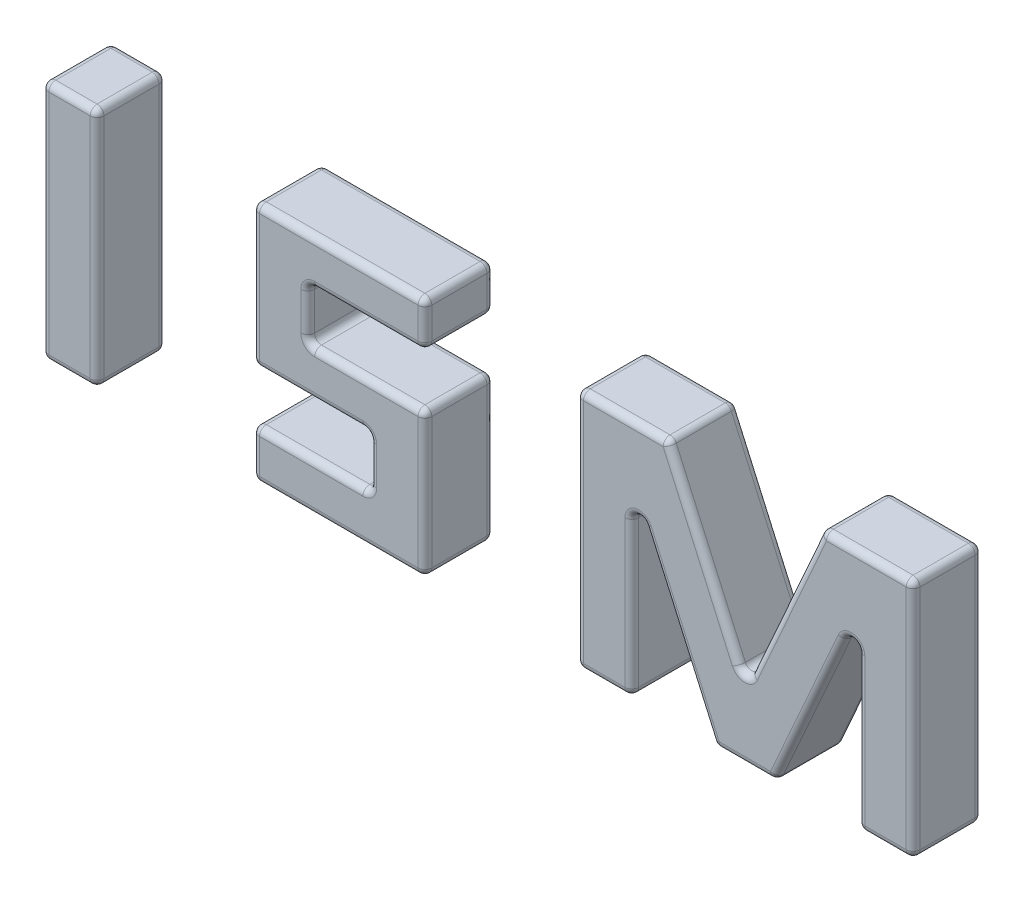
SolidWorks part; units mm, degrees
ref_plane "Front Plane" through (0, 0, 0) normal (0, 0, 1) x (1, 0, 0)
ref_plane "Top Plane" through (0, 0, 0) normal (0, 1, 0) x (1, 0, 0)
ref_plane "Right Plane" through (0, 0, 0) normal (1, 0, 0) x (0, 0, -1)
sketch "Sketch1" plane through (0, 0, 0) normal (0, 0, 1) x (1, 0, 0)
  line L0 (0, 0) -> (97.6044, 0) construction
  line L1 (0, 0) -> (0, 35) construction
  line L2 (0, 0) -> (0, 35)
  line L3 (0, 35) -> (8, 35)
  line L4 (8, 35) -> (8, 0)
  line L5 (8, 0) -> (0, 0)
  line L6 (55.565, 35) -> (30.565, 35)
  line L7 (0, 35) -> (130, 35) construction
  line L8 (130, 35) -> (130, 0) construction
  line L9 (30.565, 0) -> (55.565, 0)
  line L10 (55.565, 0) -> (55.565, 21)
  line L11 (30.565, 35) -> (30.565, 14.5)
  line L12 (55.565, 35) -> (55.565, 28.5)
  line L13 (55.565, 28.5) -> (38.565, 28.5)
  line L14 (38.565, 28.5) -> (38.565, 21)
  line L15 (38.565, 21) -> (55.565, 21)
  line L16 (30.565, 14.5) -> (47.565, 14.5)
  line L17 (47.565, 14.5) -> (47.565, 7)
  line L18 (47.565, 7) -> (30.565, 7)
  line L19 (30.565, 7) -> (30.565, 0)
  line L20 (85.5802, 27.0067) -> (97.6044, 0)
  line L21 (55.565, 35) -> (77.565, 35)
  line L22 (77.565, 35) -> (77.565, 0)
  line L23 (77.565, 0) -> (85.5802, 0)
  line L24 (85.5802, 0) -> (85.5802, 27.0067)
  line L25 (106.3615, 0) -> (130, 0) construction
  line L28 (90.7785, 35) -> (77.565, 35)
  line L29 (97.6044, 0) -> (106.3615, 0)
  line L30 (113.1874, 35) -> (126.4008, 35)
  line L32 (90.7785, 35) -> (101.9829, 9.8344)
  line L33 (113.1874, 35) -> (101.9829, 9.8344)
  line L34 (118.3856, 27.0067) -> (106.3615, 0)
  line L35 (118.3856, 0) -> (118.3856, 27.0067)
  line L36 (126.4008, 0) -> (118.3856, 0)
  line L37 (126.4008, 35) -> (126.4008, 0)
extrude "Boss-Extrude1" add sketch "Sketch1" along normal blind 10 contours L5 L4 L3 L2 | L18 L19 L9 L10 L15 L14 L13 L12 L6 L11 L16 L17 | L37 L30 L33 L32 L28 L22 L23 L24 L20 L29 L34 L35 L36
fillet "Fillet1" radius 1 12 edges at (8, 0, 5) (8, 35, 5) (0, 35, 5) (0, 0, 5) (0, 17.5, 10) (4, 35, 10) (8, 17.5, 10) (4, 0, 10) (0, 17.5, 0) (4, 35, 0) (8, 17.5, 0) (4, 0, 0)
fillet "Fillet2" radius 1 36 edges at (30.565, 7, 5) (30.565, 0, 5) (55.565, 0, 5) (55.565, 21, 5) (38.565, 21, 5) (38.565, 28.5, 5) (55.565, 28.5, 5) (55.565, 35, 5) (30.565, 35, 5) (30.565, 14.5, 5) (47.565, 14.5, 5) (47.565, 7, 5) (47.565, 10.75, 10) (39.065, 14.5, 10) (30.565, 24.75, 10) (43.065, 35, 10) (55.565, 31.75, 10) (47.065, 28.5, 10) (38.565, 24.75, 10) (47.065, 21, 10) (55.565, 10.5, 10) (43.065, 0, 10) (30.565, 3.5, 10) (39.065, 7, 10) (47.565, 10.75, 0) (39.065, 14.5, 0) (30.565, 24.75, 0) (43.065, 35, 0) (55.565, 31.75, 0) (47.065, 28.5, 0) (38.565, 24.75, 0) (47.065, 21, 0) (55.565, 10.5, 0) (43.065, 0, 0) (30.565, 3.5, 0) (39.065, 7, 0)
fillet "Fillet3" radius 1 39 edges at (126.4008, 35, 5) (113.1874, 35, 5) (101.9829, 9.8344, 5) (90.7785, 35, 5) (77.565, 35, 5) (77.565, 0, 5) (85.5802, 0, 5) (85.5802, 27.0067, 5) (97.6044, 0, 5) (106.3615, 0, 5) (118.3856, 27.0067, 5) (118.3856, 0, 5) (126.4008, 0, 5) (122.3932, 0, 10) (118.3856, 13.5034, 10) (112.3735, 13.5034, 10) (101.9829, 0, 10) (91.5923, 13.5034, 10) (85.5802, 13.5034, 10) (81.5726, 0, 10) (77.565, 17.5, 10) (84.1717, 35, 10) (96.3807, 22.4172, 10) (107.5851, 22.4172, 10) (119.7941, 35, 10) (126.4008, 17.5, 10) (122.3932, 0, 0) (118.3856, 13.5034, 0) (112.3735, 13.5034, 0) (101.9829, 0, 0) (91.5923, 13.5034, 0) (85.5802, 13.5034, 0) (81.5726, 0, 0) (77.565, 17.5, 0) (84.1717, 35, 0) (96.3807, 22.4172, 0) (107.5851, 22.4172, 0) (119.7941, 35, 0) (126.4008, 17.5, 0)
